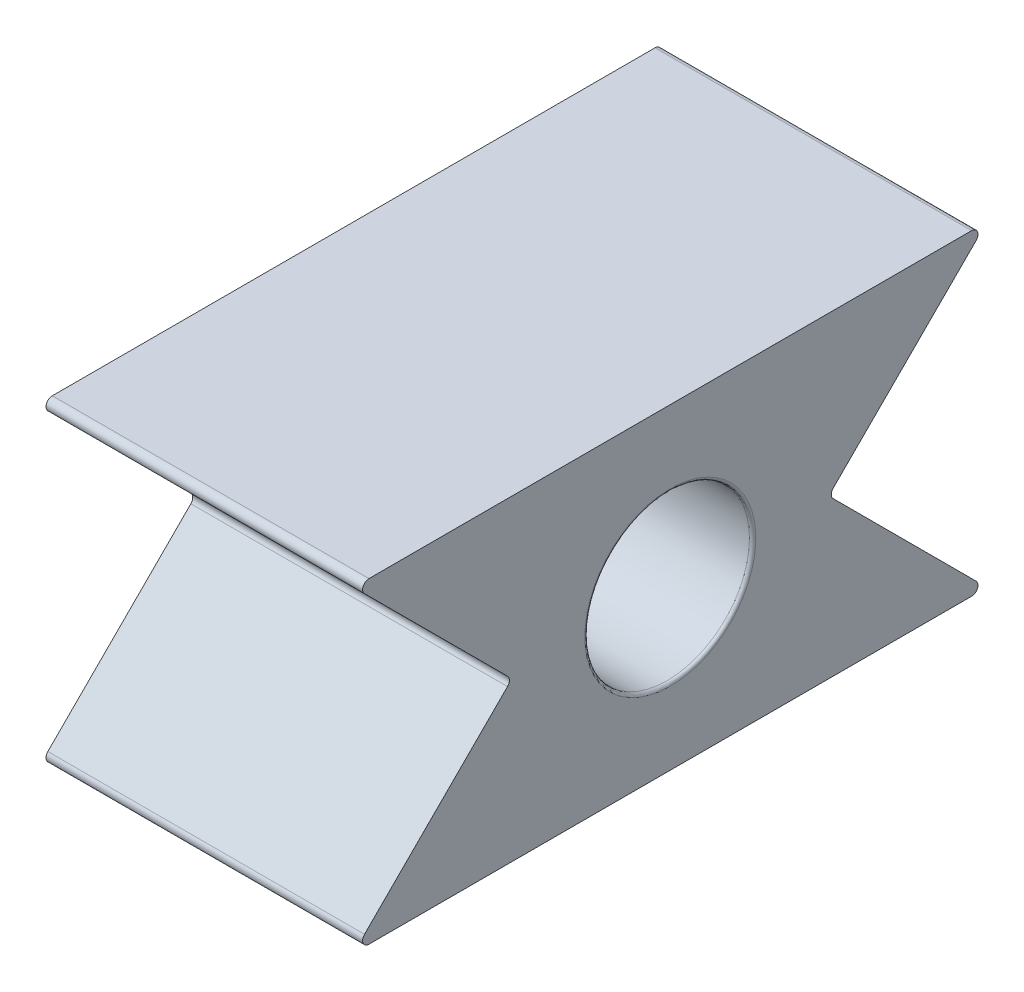
SolidWorks part; units mm, degrees
ref_plane "Alzado" through (0, 0, 0) normal (1, 0, 0) x (0, 1, 0)
ref_plane "Planta" through (0, 0, 0) normal (0, 0, 1) x (0, 1, 0)
ref_plane "Vista lateral" through (0, 0, 0) normal (0, 1, 0) x (-1, 0, 0)
sketch "Croquis1" plane through (0, 0, 0) normal (1, 0, 0) x (0, 1, 0)
  line L0 (5, -10) -> (5, 10)
  line L1 (5, 10) -> (0, 5)
  line L2 (0, 5) -> (-5, 10)
  line L3 (-5, 10) -> (-5, -10)
  line L4 (-5, -10) -> (0, -5)
  line L5 (0, -5) -> (5, -10)
  line L6 (0, 0) -> (0, 3.1131) construction
  line L7 (0, 0) -> (1.7794, 0) construction
  circle A0 centre (0, 0) radius 2.6
  point P12 (5, 0)
  dimension "D4" = 5.2
  dimension "D1" = 20
  dimension "D2" = 10
  dimension "D3" = 10
extrude "Saliente-Extruir1" add sketch "Croquis1" along normal blind 10
fillet "Redondeo1" radius 0.2 6 edges at (5, 0, -5) (5, 0, 5) (5, -5, -10) (5, 5, -10) (5, 5, 10) (5, -5, 10)
fillet "Redondeo2" radius 0.1 2 edges at (0, 0, -2.6) (10, 0, -2.6)
